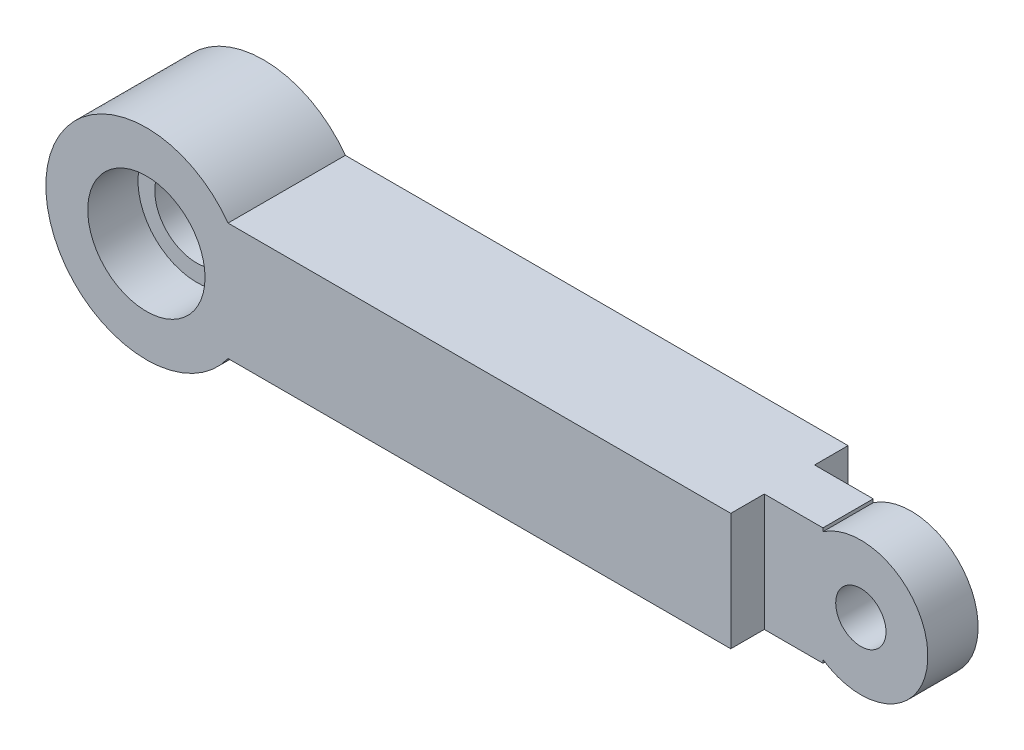
SolidWorks part; units mm, degrees
ref_plane "前视基准面" through (0, 0, 0) normal (0, 0, 1) x (1, 0, 0)
ref_plane "上视基准面" through (0, 0, 0) normal (0, 1, 0) x (1, 0, 0)
ref_plane "右视基准面" through (0, 0, 0) normal (1, 0, 0) x (0, 0, -1)
sketch "草图1" plane through (0, 0, 0) normal (0, 0, 1) x (1, 0, 0)
  line L1 (-150, 35) -> (150, 35)
  line L2 (-150, 35) -> (-150, -35)
  line L3 (-150, -35) -> (150, -35)
  line L4 (150, 35) -> (150, -35)
  line L5 (-150, 35) -> (150, -35) construction
  line L6 (-150, -35) -> (150, 35) construction
  point P0 (0, 0)
  dimension "D1" = 300
  dimension "D2" = 70
extrude "凸台-拉伸1" add sketch "草图1" along normal blind 70
sketch "草图2" plane through (0, 0, 0) normal (0, 0, -1) x (-1, 0, 0)
  circle A0 centre (198.734, 0) radius 60
  dimension "D1" = 120
extrude "凸台-拉伸2" add sketch "草图2" against normal blind 70
sketch "草图3" plane through (0, 35, 0) normal (0, 1, 0) x (1, 0, 0)
  line L0 (150, -35) -> (398.0904, -35) construction
  line L1 (150, -70) -> (150, 0) construction
  line L2 (185, -20) -> (150, -20)
  line L3 (185, -20) -> (185, -50)
  line L4 (150, -20) -> (150, -50)
  line L5 (185, -50) -> (150, -50)
  line L6 (185, -20) -> (150, -50) construction
  line L7 (150, -20) -> (185, -50) construction
  point P5 (167.5, -35)
  dimension "D1" = 30
  dimension "D2" = 0
  dimension "D3" = 35
  dimension "D4" = 0
extrude "凸台-拉伸3" add sketch "草图3" against normal up to surface (70 mm away) up to face at (0, -35, 35)
sketch "草图5" plane through (0, 0, 50) normal (0, 0, 1) x (1, 0, 0)
  line L0 (185, 35) -> (185, 33) construction
  line L1 (185, -35) -> (185, 35) construction
  line L2 (185, -35) -> (185, -33) construction
  circle A0 centre (207.6053, 0) radius 40
  dimension "D3" = 80
  dimension "D1" = 2
  dimension "D2" = 2
extrude "凸台-拉伸5" add sketch "草图5" against normal up to surface (30 mm away) up to face at (167.5, 0, 20)
sketch "草图6" plane through (0, 0, 20) normal (0, 0, -1) x (-1, 0, 0)
  line L5 (-185, 35) -> (-185, 33)
  line L6 (-185, -33) -> (-185, -35)
  line L7 (-185, -35) -> (-150, -35)
  line L8 (-150, -35) -> (-150, 35)
  line L9 (-150, 35) -> (-185, 35)
  line L10 (-185, 35) -> (-185, 33)
  line L11 (-185, -33) -> (-185, -35)
  line L12 (-185, -35) -> (-150, -35)
  line L13 (-150, -35) -> (-150, 35)
  line L14 (-150, 35) -> (-185, 35)
  circle A0 centre (-207.6053, 0) radius 15
  arc A1 (-185, 33) -> (-185, -33) centre (-207.6053, 0) ccw
  arc A2 (-185, 33) -> (-185, -33) centre (-207.6053, 0) ccw
  dimension "D2" = 30
  dimension "D1" = 0
extrude "切除-拉伸1" cut sketch "草图6" against normal through all contours A0
sketch "草图7" plane through (0, 0, 0) normal (0, 0, -1) x (-1, 0, 0)
  line L3 (-150, -35) -> (150, -35)
  line L4 (150, 35) -> (-150, 35)
  line L5 (-150, 35) -> (-150, -35)
  line L6 (-150, -35) -> (150, -35)
  line L7 (150, 35) -> (-150, 35)
  line L8 (-150, 35) -> (-150, -35)
  circle A0 centre (198.734, 0) radius 17.25 construction
  arc A1 (150, -35) -> (150, 35) centre (198.734, 0) ccw
  arc A2 (150, -35) -> (150, 35) centre (198.734, 0) ccw
  circle A3 centre (215.984, 0) radius 2
  circle A4 centre (207.359, -14.9389) radius 2
  circle A5 centre (190.109, -14.9389) radius 2
  circle A6 centre (181.484, 0) radius 2
  circle A7 centre (190.109, 14.9389) radius 2
  circle A8 centre (207.359, 14.9389) radius 2
  point P9 (0, 0)
  point P10 (330.9017, 0)
  point P20 (198.734, 0)
  dimension "D2" = 34.5
  dimension "D3" = 4
  dimension "D1" = 0
  dimension "D4" = 6
extrude "切除-拉伸2" cut sketch "草图7" against normal through all contours A8 | A7 | A6 | A5 | A4 | A3
sketch "草图8" plane through (0, 0, 70) normal (0, 0, 1) x (1, 0, 0)
  line L3 (150, 35) -> (-150, 35)
  line L4 (-150, -35) -> (150, -35)
  line L5 (150, -35) -> (150, 35)
  line L6 (150, 35) -> (-150, 35)
  line L7 (-150, -35) -> (150, -35)
  line L8 (150, -35) -> (150, 35)
  circle A0 centre (-198.734, 0) radius 25
  arc A1 (-150, 35) -> (-150, -35) centre (-198.734, 0) ccw
  arc A5 (-150, 35) -> (-150, -35) centre (-198.734, 0) ccw
  point P7 (-272.5026, 0)
  dimension "D2" = 50
  dimension "D1" = 0
extrude "切除-拉伸3" cut sketch "草图8" against normal blind 50 contours A0
sketch "草图9" plane through (0, 0, 70) normal (0, 0, 1) x (1, 0, 0)
  line L3 (150, 35) -> (-150, 35)
  line L4 (-150, -35) -> (150, -35)
  line L5 (150, -35) -> (150, 35)
  line L6 (150, 35) -> (-150, 35)
  line L7 (-150, -35) -> (150, -35)
  line L8 (150, -35) -> (150, 35)
  circle A0 centre (-198.734, 0) radius 35
  arc A1 (-150, 35) -> (-150, -35) centre (-198.734, 0) ccw
  arc A5 (-150, 35) -> (-150, -35) centre (-198.734, 0) ccw
  point P7 (-272.5484, 0)
  dimension "D2" = 70
  dimension "D1" = 0
extrude "切除-拉伸4" cut sketch "草图9" against normal blind 30 contours A0
